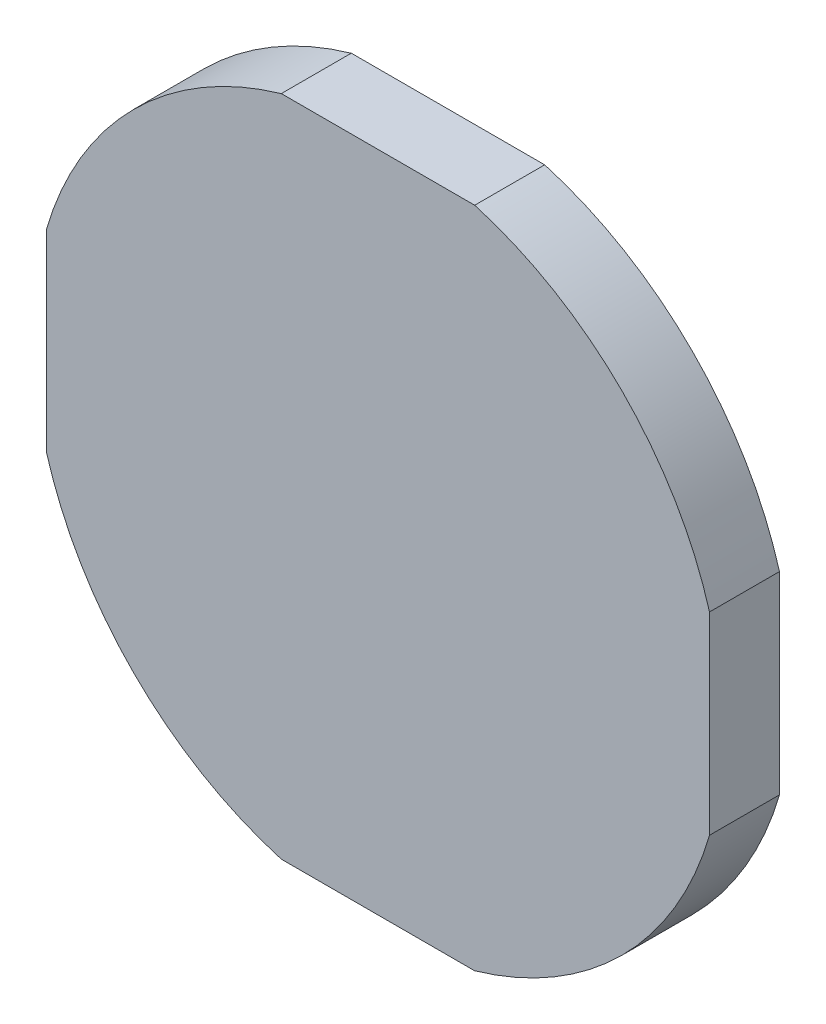
SolidWorks part; units mm, degrees
ref_plane "Front Plane" through (0, 0, 0) normal (0, 0, 1) x (1, 0, 0)
ref_plane "Top Plane" through (0, 0, 0) normal (0, 1, 0) x (1, 0, 0)
ref_plane "Right Plane" through (0, 0, 0) normal (1, 0, 0) x (0, 0, -1)
sketch "Sketch1" plane through (0, 0, 0) normal (0, 0, 1) x (1, 0, 0)
  line L0 (-1.3335, 4.572) -> (1.3335, 4.572)
  line L1 (4.572, 1.3335) -> (4.572, -1.3335)
  line L2 (1.3335, -4.572) -> (-1.3335, -4.572)
  line L3 (-4.572, 1.3335) -> (-4.572, -1.3335)
  arc A0 (-1.3335, 4.572) -> (-4.572, 1.3335) centre (0, 0) ccw
  arc A1 (4.572, 1.3335) -> (1.3335, 4.572) centre (0, 0) ccw
  arc A2 (1.3335, -4.572) -> (4.572, -1.3335) centre (0, 0) ccw
  arc A3 (-4.572, -1.3335) -> (-1.3335, -4.572) centre (0, 0) ccw
  dimension "D1" = 9.525
  dimension "D2" = 9.144
extrude "Boss-Extrude1" add sketch "Sketch1" against normal blind 0.9652
sketch "Sketch2" plane through (0, 0, -0.9652) normal (0, 0, -1) x (-1, 0, 0)
  line L0 (0, 0.625) -> (0, 0) construction
  line L1 (-2.625, 3.125) -> (-1.375, 3.125)
  line L2 (-2.625, 3.125) -> (-2.625, 0.625)
  line L3 (-2.625, 0.625) -> (-1.375, 0.625)
  line L4 (-1.375, 3.125) -> (-1.375, 0.625)
  line L5 (-0.625, 3.125) -> (0.625, 3.125)
  line L6 (-0.625, 3.125) -> (-0.625, 0.625)
  line L7 (-0.625, 0.625) -> (0.625, 0.625)
  line L8 (0.625, 3.125) -> (0.625, 0.625)
  line L9 (1.375, 3.125) -> (2.625, 3.125)
  line L10 (1.375, 3.125) -> (1.375, 0.625)
  line L11 (1.375, 0.625) -> (2.625, 0.625)
  line L12 (2.625, 3.125) -> (2.625, 0.625)
  line L13 (-2.625, -0.625) -> (-1.375, -0.625)
  line L14 (-2.625, -0.625) -> (-2.625, -3.125)
  line L15 (-2.625, -3.125) -> (-1.375, -3.125)
  line L16 (-1.375, -0.625) -> (-1.375, -3.125)
  line L17 (-0.625, -0.625) -> (0.625, -0.625)
  line L18 (-0.625, -0.625) -> (-0.625, -3.125)
  line L19 (-0.625, -3.125) -> (0.625, -3.125)
  line L20 (0.625, -0.625) -> (0.625, -3.125)
  line L21 (1.375, -0.625) -> (2.625, -0.625)
  line L22 (1.375, -0.625) -> (1.375, -3.125)
  line L23 (1.375, -3.125) -> (2.625, -3.125)
  line L24 (2.625, -0.625) -> (2.625, -3.125)
  line L25 (0, 0) -> (0, -0.625) construction
  line L26 (-0.625, 1.875) -> (-1.375, 1.875) construction
  line L27 (0.625, 1.875) -> (1.375, 1.875) construction
  line L28 (-1.375, -1.875) -> (-0.625, -1.875) construction
  line L29 (0.625, -1.875) -> (1.375, -1.875) construction
  dimension "D1" = 2
  dimension "D2" = 1.25
  dimension "D3" = 2.5
  dimension "D4" = 1.25
extrude "Cut-Extrude1" cut sketch "Sketch2" against normal blind 0.0254
